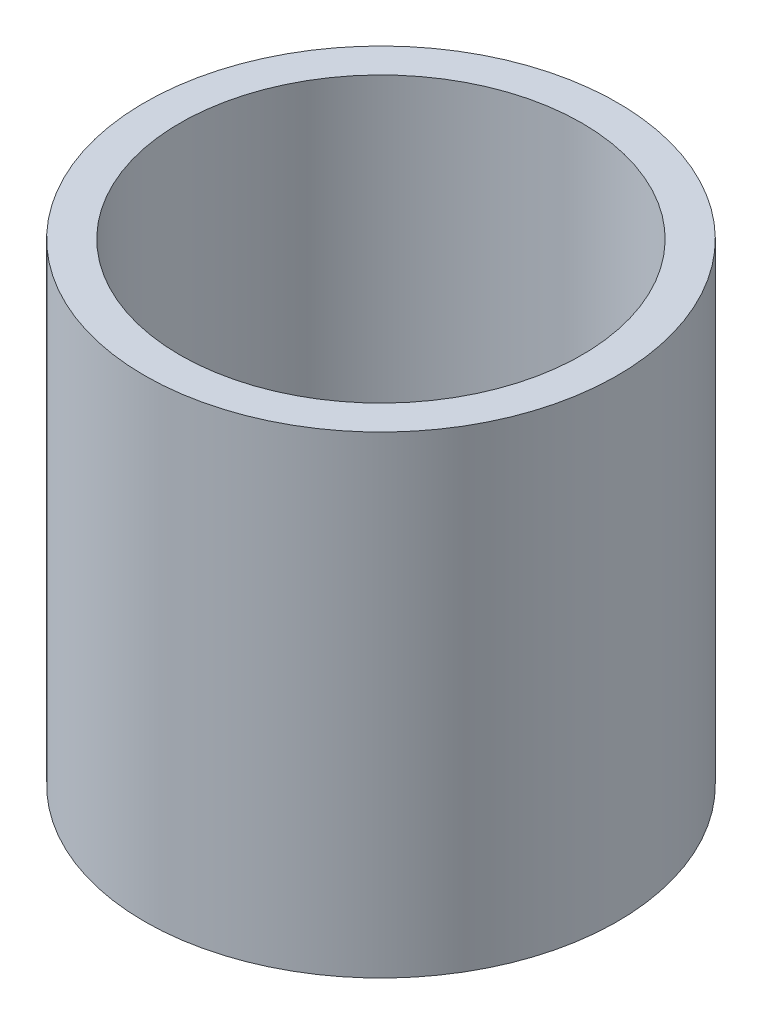
SolidWorks part; units mm, degrees
ref_plane "정면" through (0, 0, 0) normal (0, 0, 1) x (1, 0, 0)
ref_plane "윗면" through (0, 0, 0) normal (0, 1, 0) x (1, 0, 0)
ref_plane "우측면" through (0, 0, 0) normal (1, 0, 0) x (0, 0, -1)
sketch "스케치1" plane through (0, 0, 0) normal (0, 1, 0) x (1, 0, 0)
  circle A0 centre (0, 0) radius 20
  circle A1 centre (0, 0) radius 17
  dimension "D1" = 40
  dimension "D2" = 3
extrude "보스-돌출1" add sketch "스케치1" along normal blind 40
